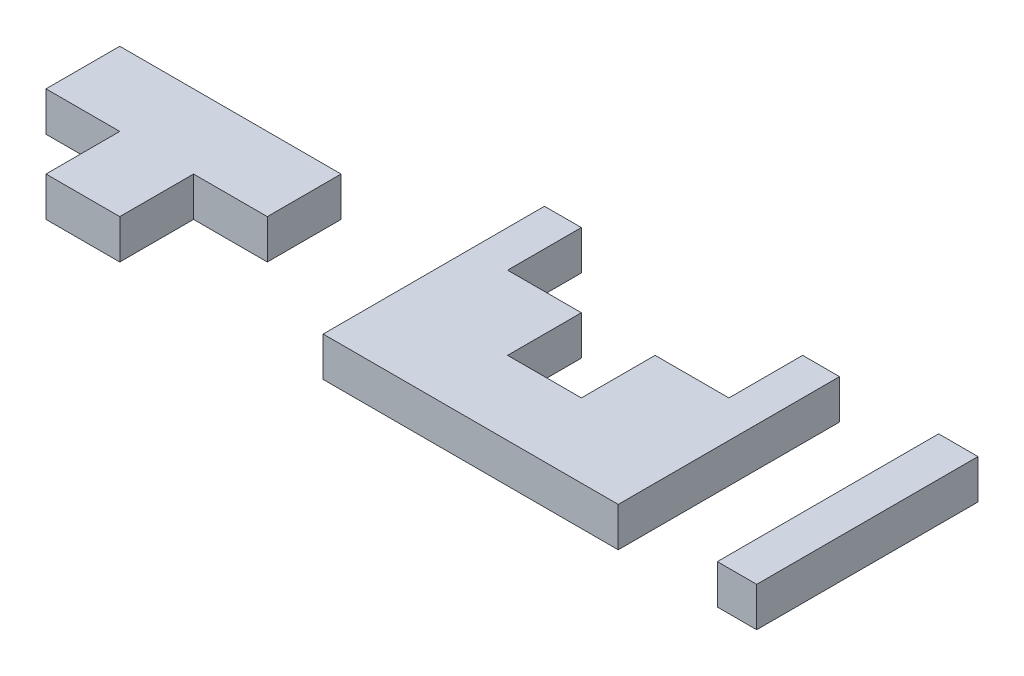
SolidWorks part; units mm, degrees
ref_plane "Front Plane" through (0, 0, 0) normal (0, 0, 1) x (1, 0, 0)
ref_plane "Top Plane" through (0, 0, 0) normal (0, 1, 0) x (1, 0, 0)
ref_plane "Right Plane" through (0, 0, 0) normal (1, 0, 0) x (0, 0, -1)
sketch "Sketch1" plane through (0, 0, 0) normal (0, 1, 0) x (1, 0, 0)
  line L0 (-31.3316, 0) -> (-16.3316, 0)
  line L1 (-16.3316, 0) -> (-16.3316, 15)
  line L2 (-16.3316, 15) -> (-1.3316, 15)
  line L3 (-1.3316, 15) -> (-1.3316, 30)
  line L4 (-1.3316, 30) -> (-46.3316, 30)
  line L5 (-46.3316, 30) -> (-46.3316, 15)
  line L6 (-46.3316, 15) -> (-31.3316, 15)
  line L7 (-31.3316, 15) -> (-31.3316, 0)
  line L8 (25.0261, 45) -> (25.0261, 0)
  line L9 (25.0261, 0) -> (85.0261, 0)
  line L10 (85.0261, 0) -> (85.0261, 45)
  line L11 (85.0261, 45) -> (77.5261, 45)
  line L12 (77.5261, 45) -> (77.5261, 30)
  line L13 (77.5261, 30) -> (62.5261, 30)
  line L14 (62.5261, 30) -> (62.5261, 15)
  line L15 (62.5261, 15) -> (47.5261, 15)
  line L16 (47.5261, 15) -> (47.5261, 30)
  line L17 (47.5261, 30) -> (32.5261, 30)
  line L18 (32.5261, 30) -> (32.5261, 45)
  line L19 (32.5261, 45) -> (25.0261, 45)
  line L21 (105.1773, 45) -> (113.1773, 45)
  line L22 (105.1773, 45) -> (105.1773, 0)
  line L23 (105.1773, 0) -> (113.1773, 0)
  line L24 (113.1773, 45) -> (113.1773, 0)
  dimension "D1" = 45
  dimension "D2" = 15
  dimension "D3" = 15
  dimension "D4" = 15
  dimension "D5" = 15
  dimension "D6" = 60
  dimension "D7" = 7.5
  dimension "D8" = 7.5
  dimension "D9" = 45
  dimension "D10" = 45
  dimension "D11" = 15
  dimension "D12" = 15
  dimension "D13" = 15
  dimension "D14" = 15
  dimension "D15" = 15
  dimension "D16" = 8
extrude "Boss-Extrude1" add sketch "Sketch1" along normal blind 8
